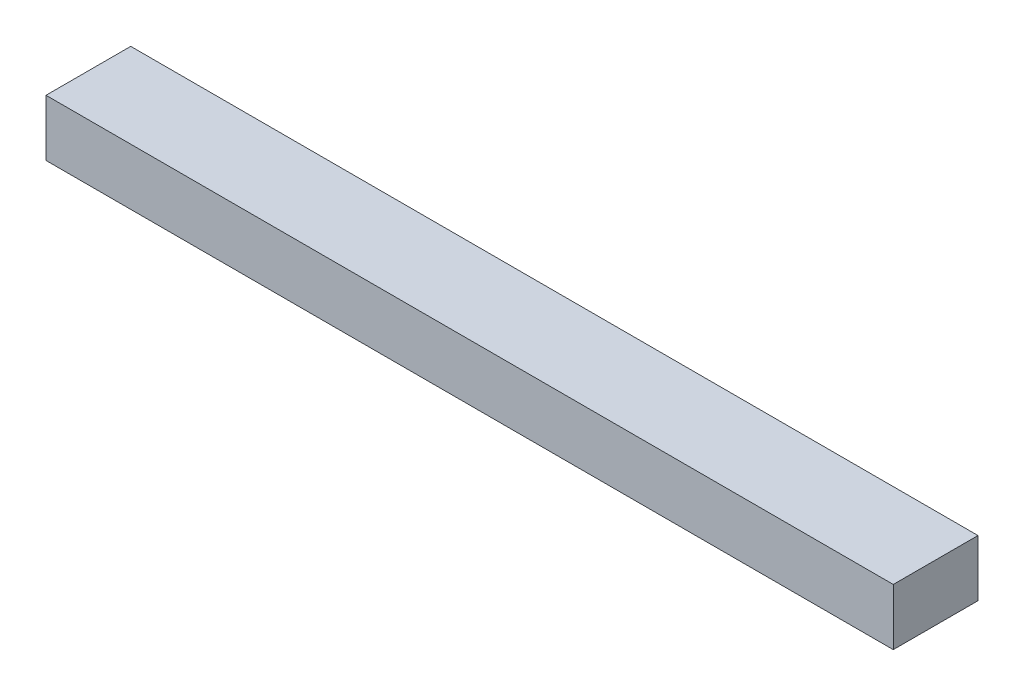
SolidWorks part; units mm, degrees
ref_plane "Front Plane" through (0, 0, 0) normal (0, 0, 1) x (1, 0, 0)
ref_plane "Top Plane" through (0, 0, 0) normal (0, 1, 0) x (1, 0, 0)
ref_plane "Right Plane" through (0, 0, 0) normal (1, 0, 0) x (0, 0, -1)
sketch "Sketch1" plane through (0, 0, 0) normal (0, 1, 0) x (1, 0, 0)
  line L1 (0, 0) -> (190.5, 0)
  line L2 (0, 0) -> (0, 19.05)
  line L3 (0, 19.05) -> (190.5, 19.05)
  line L4 (190.5, 0) -> (190.5, 19.05)
  dimension "D1" = 19.05
  dimension "D2" = 190.5
extrude "Boss-Extrude1" add sketch "Sketch1" along normal blind 12.7
